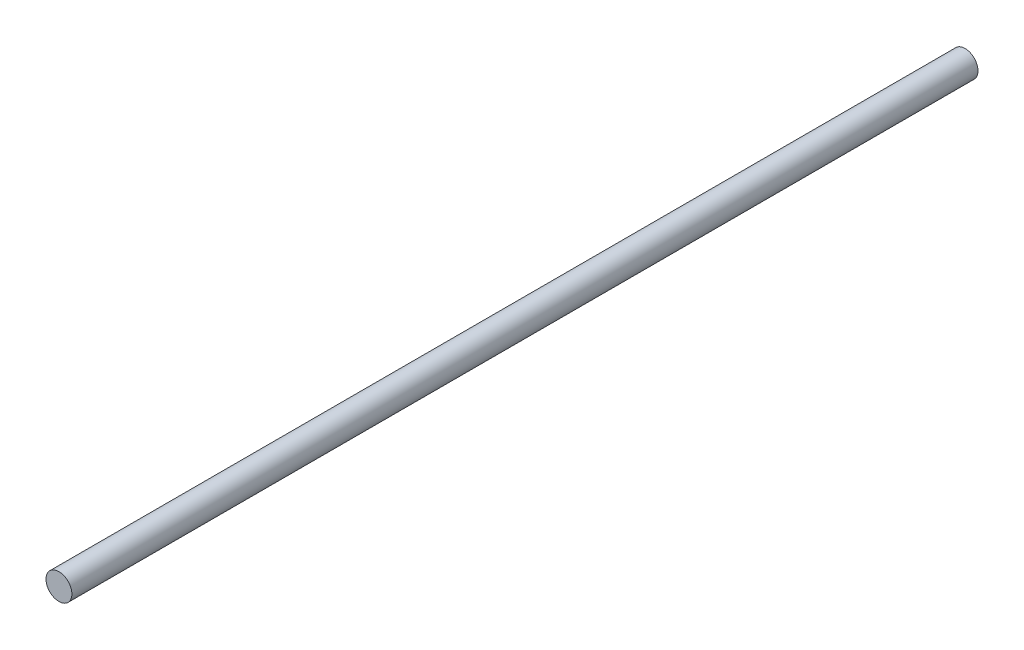
SolidWorks part; units mm, degrees
material "Литая легированная сталь"
ref_plane "Спереди" through (0, 0, 0) normal (0, 0, 1) x (1, 0, 0)
ref_plane "Сверху" through (0, 0, 0) normal (0, 1, 0) x (1, 0, 0)
ref_plane "Справа" through (0, 0, 0) normal (1, 0, 0) x (0, 0, -1)
sketch "Эскиз1" plane through (0, 0, 0) normal (0, 1, 0) x (1, 0, 0)
  line L0 (4, 0) -> (0, 0)
  line L1 (0, 0) -> (0, -280)
  line L2 (0, -280) -> (4, -280)
  line L3 (4, -280) -> (4, 0)
  line L4 (0, 0) -> (0, -280) construction
revolve "Повернуть1" add sketch "Эскиз1" angle 360 about L4
